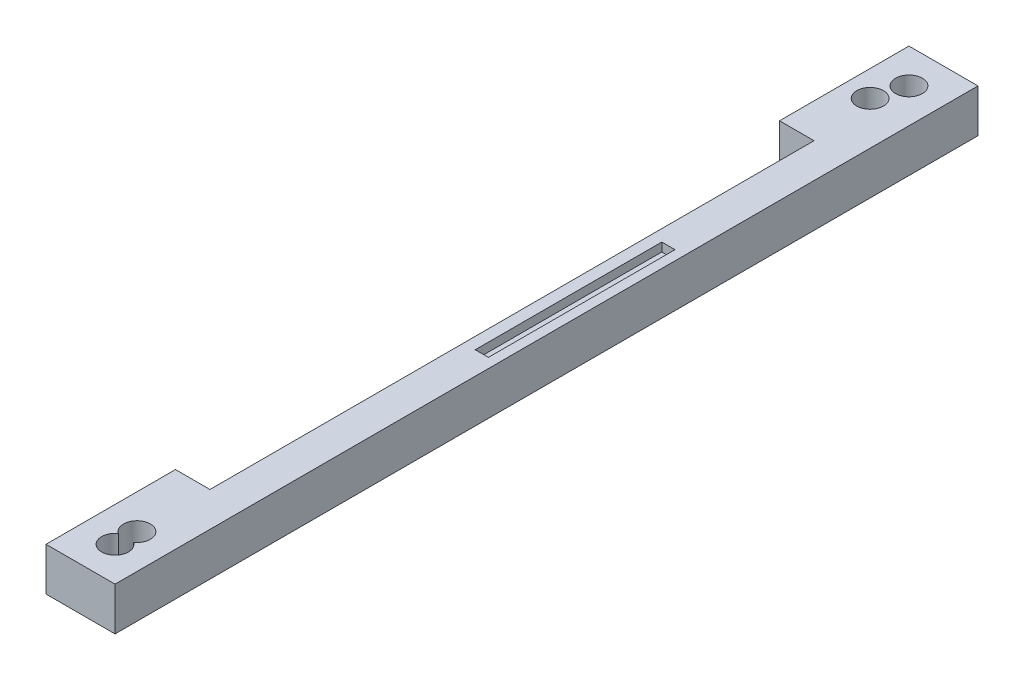
SolidWorks part; units mm, degrees
ref_plane "Ebene vorne" through (0, 0, 0) normal (0, 0, 1) x (1, 0, 0)
ref_plane "Ebene oben" through (0, 0, 0) normal (0, 1, 0) x (1, 0, 0)
ref_plane "Ebene rechts" through (0, 0, 0) normal (1, 0, 0) x (0, 0, -1)
sketch "Sketch1" plane through (0, 0, 0) normal (0, 1, 0) x (1, 0, 0)
  line L1 (-4, -50) -> (4, -50)
  line L2 (-4, -50) -> (-4, 50)
  line L3 (-4, 50) -> (4, 50)
  line L4 (4, -50) -> (4, 50)
  line L5 (-4, -50) -> (4, 50) construction
  line L6 (-4, 50) -> (4, -50) construction
  point P0 (0, 0)
  dimension "D1" = 8
  dimension "D2" = 100
extrude "Extrude1" add sketch "Sketch1" along normal blind 5
sketch "Sketch2" plane through (0, 5, 0) normal (0, 1, 0) x (1, 0, 0)
  line L1 (-4, -50) -> (4, -50) construction
  circle A0 centre (0, -46) radius 1.55
  dimension "D1" = 3.1
  dimension "D2" = 4
extrude "Extrude4" cut sketch "Sketch2" against normal blind 5
sketch "Sketch4" plane through (0, 5, 0) normal (0, 1, 0) x (1, 0, 0)
  line L0 (4, -50) -> (4, 50) construction
  line L3 (4, 50) -> (-4, 50) construction
  circle A0 centre (0, -43.46) radius 1.55
  circle A1 centre (0, -46) radius 1.55 construction
  circle A2 centre (-1, 42.5) radius 1.55
  circle A3 centre (0, 46) radius 1.55
  circle M2 centre (0, -46) radius 1.55
  dimension "D1" = 5
  dimension "D2" = 2.54
  dimension "D3" = 3.1
  dimension "D4" = 4
  dimension "D5" = 4
  dimension "D6" = 3.5
extrude "Extrude6" cut sketch "Sketch4" against normal blind 5 contours A0 M2 | A2 | A3
sketch "Sketch5" plane through (0, 5, 0) normal (0, 1, 0) x (1, 0, 0)
  line L0 (-4, 50) -> (-4, -50) construction
  line L1 (-4, 35) -> (0, 35)
  line L2 (-4, 35) -> (-4, -35)
  line L3 (-4, -35) -> (0, -35)
  line L4 (0, 35) -> (0, -35)
  line L5 (4, 50) -> (-4, 50) construction
  dimension "D1" = 70
  dimension "D2" = 4
  dimension "D3" = 15
extrude "Extrude7" cut sketch "Sketch5" against normal blind 5
sketch "Sketch6" plane through (0, 5, 0) normal (0, 1, 0) x (1, 0, 0)
  line L1 (2.8779, -5.6079) -> (1.3474, -5.6079)
  line L2 (2.8779, -5.6079) -> (2.8779, 16.0106)
  line L3 (2.8779, 16.0106) -> (1.3474, 16.0106)
  line L4 (1.3474, -5.6079) -> (1.3474, 16.0106)
extrude "Extrude8" cut sketch "Sketch6" against normal blind 1
